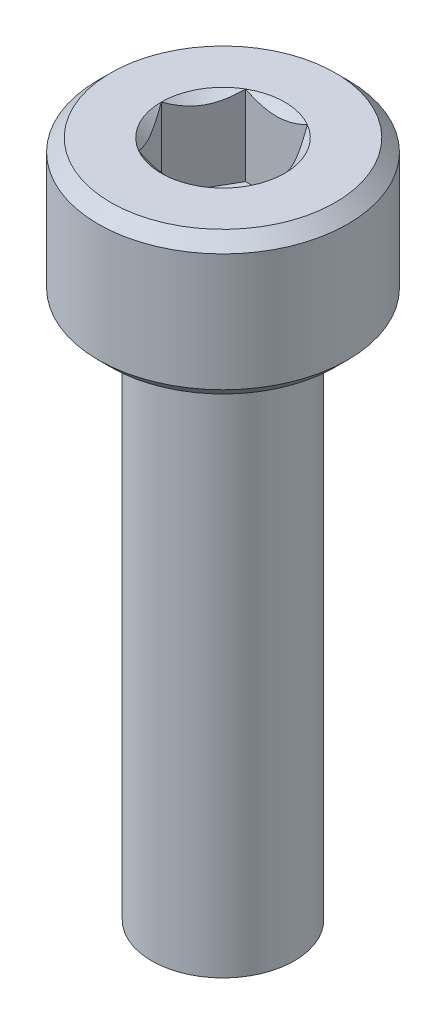
SolidWorks part; units mm, degrees
ref_plane "Front" through (0, 0, 0) normal (0, 0, 1) x (1, 0, 0)
ref_plane "Top" through (0, 0, 0) normal (0, 1, 0) x (1, 0, 0)
ref_plane "Right" through (0, 0, 0) normal (1, 0, 0) x (0, 0, -1)
sketch "Sketch1" plane through (0, 0, 0) normal (0, 1, 0) x (1, 0, 0)
  circle A0 centre (0, 0) radius 3.5
  dimension "D1" = 7
extrude "Boss-Extrude1" add sketch "Sketch1" along normal blind 4
sketch "Sketch2" plane through (0, 4, 0) normal (0, 1, 0) x (1, 0, 0)
  line L1 (0.866, 1.5) -> (-0.866, 1.5)
  line L2 (-0.866, 1.5) -> (-1.7321, 0)
  line L3 (-1.7321, 0) -> (-0.866, -1.5)
  line L4 (-0.866, -1.5) -> (0.866, -1.5)
  line L5 (0.866, -1.5) -> (1.7321, 0)
  line L6 (1.7321, 0) -> (0.866, 1.5)
  circle A0 centre (0, 0) radius 1.5 construction
  point P10 (0, 1.5)
  dimension "D1" = 3
extrude "Cut-Extrude1" cut sketch "Sketch2" against normal blind 2.25
sketch "Sketch3" plane through (0, 4, 0) normal (0, 1, 0) x (1, 0, 0)
  circle A0 centre (0, 0) radius 1.7321
extrude "Cut-Extrude2" cut sketch "Sketch3" against normal through all draft 45
chamfer "Chamfer1" distance 0.35 angle 45 2 edges at (0, 0, 3.5) (0, 4, 3.5)
sketch "草图1" plane through (0, 0, 0) normal (0, -1, 0) x (-1, 0, 0)
  circle A0 centre (0, 0) radius 2
  dimension "D1" = 4
extrude "凸台-拉伸1" add sketch "草图1" along normal blind 15
